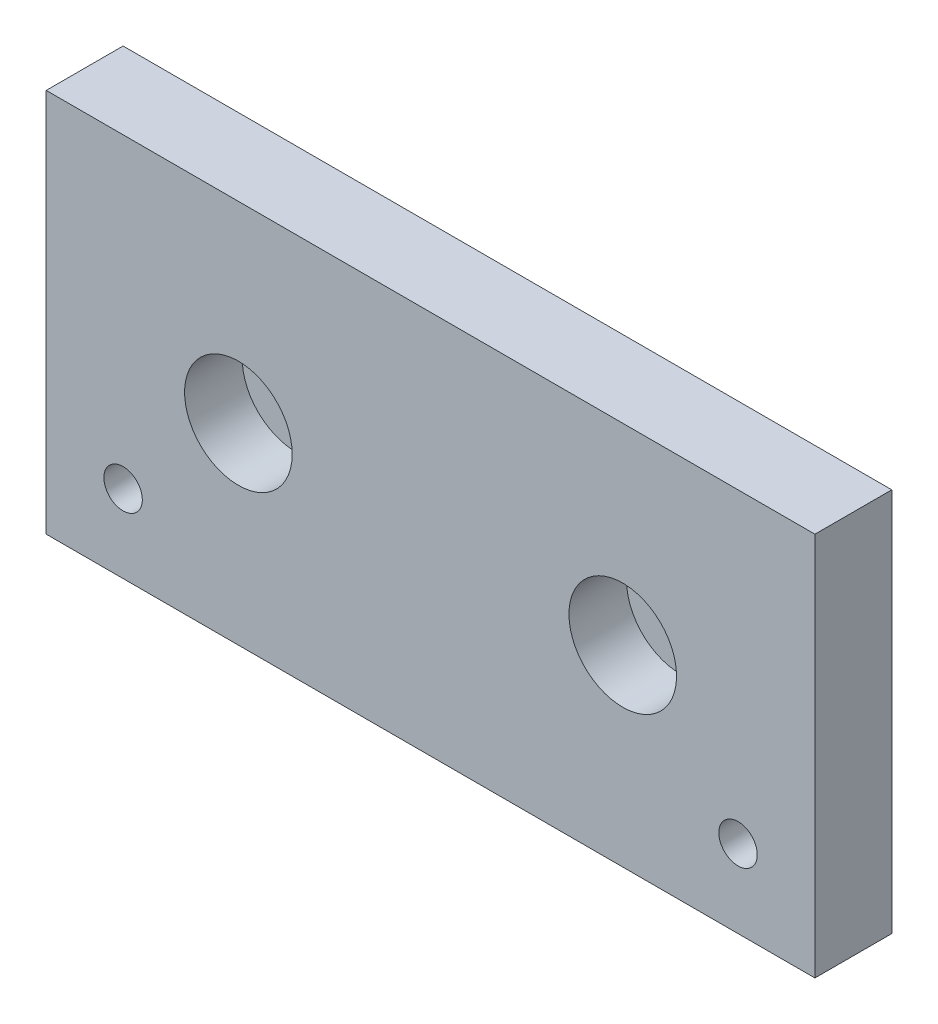
SolidWorks part; units mm, degrees
material "PVC 0.007 Plasticized"
ref_plane "Front Plane" through (0, 0, 0) normal (0, 0, 1) x (1, 0, 0)
ref_plane "Top Plane" through (0, 0, 0) normal (0, 1, 0) x (1, 0, 0)
ref_plane "Right Plane" through (0, 0, 0) normal (1, 0, 0) x (0, 0, -1)
sketch "Sketch1" plane through (0, 0, 0) normal (0, 0, 1) x (1, 0, 0)
  line L1 (100, 50) -> (-100, 50)
  line L2 (100, 50) -> (100, -50)
  line L3 (100, -50) -> (-100, -50)
  line L4 (-100, 50) -> (-100, -50)
  line L5 (100, 50) -> (-100, -50) construction
  line L6 (100, -50) -> (-100, 50) construction
  point P0 (0, 0)
  dimension "D1" = 100
  dimension "D2" = 200
extrude "Boss-Extrude1" add sketch "Sketch1" along normal blind 20
sketch "Sketch2" plane through (0, 0, 20) normal (0, 0, 1) x (1, 0, 0)
  line L0 (0, 0) -> (0, 33.7728) construction
  circle A0 centre (-50, 0) radius 14
  circle A1 centre (50, 0) radius 14
  dimension "D1" = 28
  dimension "D2" = 50
extrude "Cut-Extrude1" cut sketch "Sketch2" against normal blind 15
sketch "Sketch3" plane through (0, 0, 0) normal (0, 0, -1) x (-1, 0, 0)
  circle A0 centre (-60, -9.75) radius 14
  circle A1 centre (60, -9.75) radius 14
  dimension "D1" = 28
  dimension "D2" = 28
extrude "Cut-Extrude2" [suppressed] cut sketch "Sketch3" against normal through all
sketch "Sketch4" plane through (0, 0, 0) normal (0, 0, -1) x (-1, 0, 0)
  circle A2 centre (-80, -29.75) radius 5
  circle A4 centre (80, -29.75) radius 5
extrude "Cut-Extrude3" cut sketch "Sketch4" against normal through all
